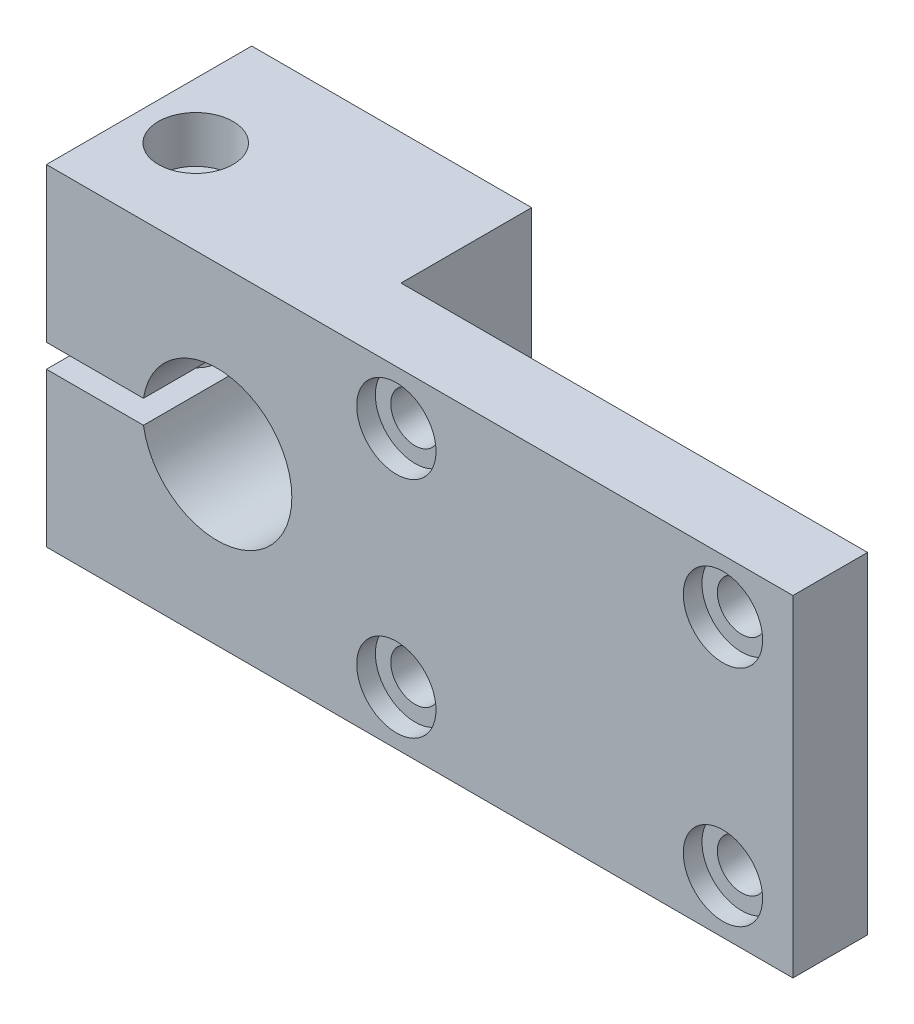
SolidWorks part; units mm, degrees
ref_plane "Plan de face" through (0, 0, 0) normal (0, 0, 1) x (1, 0, 0)
ref_plane "Plan de dessus" through (0, 0, 0) normal (0, 1, 0) x (1, 0, 0)
ref_plane "Plan de droite" through (0, 0, 0) normal (1, 0, 0) x (0, 0, -1)
sketch "Esquisse1" plane through (0, 0, 0) normal (0, 0, 1) x (1, 0, 0)
  line L4 (25, 0) -> (-25, 0)
  line L5 (-25, 0) -> (-25, -31.5)
  line L6 (-25, -31.5) -> (25, -31.5)
  line L7 (25, -31.5) -> (25, 0)
  line L8 (25, 0) -> (-25, 0)
  line L9 (-25, 0) -> (-25, -31.5)
  line L10 (-25, -31.5) -> (25, -31.5)
  line L11 (25, -31.5) -> (25, 0)
  circle A0 centre (17.5, -27.75) radius 2.1 construction
  circle A1 centre (17.5, -3.75) radius 2.1 construction
  circle A2 centre (-17.5, -3.75) radius 2.1 construction
  circle A3 centre (-17.5, -27.75) radius 2.1 construction
  circle A4 centre (17.5, -27.75) radius 2.1
  circle A5 centre (17.5, -3.75) radius 2.1
  circle A6 centre (-17.5, -3.75) radius 2.1
  circle A7 centre (-17.5, -27.75) radius 2.1
  dimension "D1" = 0
extrude "Boss.-Extru.1" add sketch "Esquisse1" along normal blind 8
sketch "Esquisse3" plane through (-25, 0, 0) normal (-1, 0, 0) x (0, 0, 1)
  line L1 (8, -31.5) -> (-36, -31.5)
  line L2 (8, -31.5) -> (8, 0)
  line L3 (8, 0) -> (-36, 0)
  line L4 (-36, -31.5) -> (-36, 0)
extrude "Boss.-Extru.2" add sketch "Esquisse3" along normal blind 30
sketch "Esquisse4" plane through (0, 0, 8) normal (0, 0, 1) x (1, 0, 0)
  line L0 (-21.7, -31.5) -> (-21.7, 0) construction
  line L1 (-55, -31.5) -> (25, -31.5) construction
  line L2 (25, 0) -> (-55, 0) construction
  line L3 (-55, -15.75) -> (-21.7, -15.75) construction
  line L4 (-55, -31.5) -> (-55, 0) construction
  circle A0 centre (-36.7, -15.75) radius 8
  circle A2 centre (-17.5, -27.75) radius 2.1 construction
  dimension "D1" = 4.2
  dimension "D2" = 16
  dimension "D3" = 15
extrude "Enlèv. mat.-Extru.1" cut sketch "Esquisse4" against normal blind 60
sketch "Esquisse6" plane through (0, 0, 8) normal (0, 0, 1) x (1, 0, 0)
  line L0 (-55, -15.75) -> (-21.7, -15.75) construction
  line L1 (-55, -31.5) -> (-55, 0) construction
  line L2 (-21.7, -15.75) -> (-21.7, 0) construction
  line L3 (25, 0) -> (-55, 0) construction
  line L4 (-55, -14.5) -> (-44.6017, -14.5)
  line L5 (-55, -17) -> (-44.6017, -17)
  line L6 (-55, -14.5) -> (-55, -17)
  circle A0 centre (-36.7, -15.75) radius 8 construction
  arc A1 (-44.6017, -14.5) -> (-44.6017, -17) centre (-36.7, -15.75) ccw
  dimension "D3" = 1.25
  dimension "D1" = 15
  dimension "D2" = 1.25
extrude "Enlèv. mat.-Extru.2" cut sketch "Esquisse6" against normal blind 56
sketch "Esquisse7" plane through (0, 0, 8) normal (0, 0, 1) x (1, 0, 0)
  circle A0 centre (-17.5, -3.75) radius 3.6
  circle A1 centre (-17.5, -27.75) radius 3.6
  circle A2 centre (17.5, -27.75) radius 3.6
  circle A3 centre (17.5, -3.75) radius 3.6
  circle A4 centre (17.5, -3.75) radius 2.1 construction
  circle A5 centre (17.5, -27.75) radius 2.1 construction
  circle A6 centre (-17.5, -27.75) radius 2.1 construction
  dimension "D1" = 7.2
  dimension "D2" = 7.2
  dimension "D3" = 7.2
  dimension "D4" = 7.2
extrude "Enlèv. mat.-Extru.3" cut sketch "Esquisse7" against normal blind 2
hole_wizard "Dégagement M51" positions "Esquisse10" profile "Esquisse11" hole size "M5" standard "Ansi Metric"
sketch "Esquisse10" plane through (0, 0, 0) normal (0, 1, 0) x (1, 0, 0)
  line L0 (-55, -8) -> (-55, 36) construction
  line L1 (25, -8) -> (-55, -8) construction
  point P0 (-49, 2)
  dimension "D1" = 6
  dimension "D2" = 10
sketch "Esquisse11" plane through (-49, 0, -2) normal (1, 0, 0) x (0, 0, 1)
  line L0 (0, 0) -> (0, 35.5923)
  line L1 (0, 35.5923) -> (2.65, 34)
  line L2 (2.65, 34) -> (2.65, 0)
  line L5 (2.65, 0) -> (0, 0)
  line L10 (0, 35.5923) -> (-2.65, 34) construction
  line L11 (0, -6.35) -> (0, 107.95) construction
  dimension "Diamètre du perçage" = 5.3
  dimension "Profondeur du perçage" = 34
  dimension "Angle de pointe" = 118
sketch "Esquisse12" plane through (0, -31.5, 0) normal (0, -1, 0) x (1, 0, 0)
  line L0 (-49, -2) -> (-49, 8) construction
  line L1 (-45, 0.3094) -> (-49, 2.6188)
  line L2 (-49, 2.6188) -> (-53, 0.3094)
  line L3 (-53, 0.3094) -> (-53, -4.3094)
  line L4 (-53, -4.3094) -> (-49, -6.6188)
  line L5 (-49, -6.6188) -> (-45, -4.3094)
  line L6 (-45, -4.3094) -> (-45, 0.3094)
  line L7 (-55, 8) -> (25, 8) construction
  line L8 (-55, -36) -> (-55, 8) construction
  circle A0 centre (-49, -2) radius 4 construction
  dimension "D3" = 10
  dimension "D1" = 8
  dimension "D2" = 10
  dimension "D4" = 6
extrude "Enlèv. mat.-Extru.4" cut sketch "Esquisse12" against normal blind 8
sketch "Esquisse13" plane through (0, -31.5, 0) normal (0, -1, 0) x (1, 0, 0)
  line L0 (-55, -36) -> (-55, 8) construction
  line L1 (-55, -14) -> (-25, -14)
  line L2 (-55, -14) -> (-55, -36)
  line L3 (-55, -36) -> (-25, -36)
  line L4 (-25, -14) -> (-25, -36)
  line L5 (-55, -36) -> (-25, -36) construction
  line L7 (-55, 8) -> (25, 8) construction
  line L8 (-25, -36) -> (-25, 0) construction
  dimension "D2" = 22
extrude "Enlèv. mat.-Extru.6" cut sketch "Esquisse13" against normal blind 58
sketch "Esquisse14" plane through (0, 0, 0) normal (0, 1, 0) x (1, 0, 0)
  circle A0 centre (-49, 2) radius 4
  dimension "D1" = 8
extrude "Enlèv. mat.-Extru.7" cut sketch "Esquisse14" against normal blind 3
sketch "Esquisse15" plane through (-55, 0, 0) normal (-1, 0, 0) x (0, 0, 1)
  line L1 (-14, 0) -> (-14, -14.5) construction
  line L2 (-14, -31.5) -> (8, -31.5) construction
  circle A0 centre (4, -20.5) radius 1.25
  dimension "D1" = 2.5
  dimension "D2" = 18
  dimension "D3" = 11
extrude "Enlèv. mat.-Extru.8" cut sketch "Esquisse15" against normal blind 5
sketch "Esquisse16" plane through (0, -31.5, 0) normal (0, -1, 0) x (1, 0, 0)
  line L0 (-53, 0.3094) -> (-53, -4.3094) construction
  line L1 (-49, 2.6188) -> (-53, 0.3094) construction
  line L2 (-45, 0.3094) -> (-49, 2.6188) construction
  line L3 (-45, -4.3094) -> (-45, 0.3094) construction
  line L4 (-49, -6.6188) -> (-45, -4.3094) construction
  line L5 (-53, -4.3094) -> (-49, -6.6188) construction
  line L6 (-55, 8) -> (-55, -14)
  line L7 (-55, -14) -> (-25, -14)
  line L8 (-25, -14) -> (-25, 0)
  line L9 (-25, 0) -> (25, 0)
  line L10 (25, 0) -> (25, 8)
  line L11 (25, 8) -> (-55, 8)
  line L12 (-55, 8) -> (-55, -14)
  line L13 (-55, -14) -> (-25, -14)
  line L14 (-25, -14) -> (-25, 0)
  line L15 (-25, 0) -> (25, 0)
  line L16 (25, 0) -> (25, 8)
  line L17 (25, 8) -> (-55, 8)
  line L18 (-53, 0.3094) -> (-53, -4.3094)
  line L19 (-49, 2.6188) -> (-53, 0.3094)
  line L20 (-45, 0.3094) -> (-49, 2.6188)
  line L21 (-45, -4.3094) -> (-45, 0.3094)
  line L22 (-49, -6.6188) -> (-45, -4.3094)
  line L23 (-53, -4.3094) -> (-49, -6.6188)
  dimension "D1" = 0
extrude "Boss.-Extru.3" add sketch "Esquisse16" along normal blind 2
sketch "Esquisse17" plane through (0, 0, 0) normal (0, 1, 0) x (1, 0, 0)
  line L6 (-25, 0) -> (-25, 14)
  line L7 (-25, 14) -> (-55, 14)
  line L8 (-55, 14) -> (-55, -8)
  line L9 (-55, -8) -> (25, -8)
  line L10 (25, -8) -> (25, 0)
  line L11 (25, 0) -> (-25, 0)
  line L12 (-25, 0) -> (-25, 14)
  line L13 (-25, 14) -> (-55, 14)
  line L14 (-55, 14) -> (-55, -8)
  line L15 (-55, -8) -> (25, -8)
  line L16 (25, -8) -> (25, 0)
  line L17 (25, 0) -> (-25, 0)
  circle A0 centre (-49, 2) radius 4 construction
  circle A1 centre (-49, 2) radius 4
  dimension "D1" = 0
extrude "Boss.-Extru.4" add sketch "Esquisse17" along normal blind 2
sketch "Esquisse18" plane through (0, 0, 8) normal (0, 0, 1) x (1, 0, 0)
  circle A0 centre (-17.5, -3.75) radius 2.6
  circle A1 centre (17.5, -3.75) radius 2.6
  circle A2 centre (17.5, -27.75) radius 2.6
  circle A3 centre (-17.5, -27.75) radius 2.6
  dimension "D1" = 5.2
  dimension "D2" = 5.2
  dimension "D3" = 5.2
  dimension "D4" = 5.2
extrude "Enlèv. mat.-Extru.9" cut sketch "Esquisse18" against normal blind 22
sketch "Esquisse19" plane through (0, 0, 8) normal (0, 0, 1) x (1, 0, 0)
  circle A0 centre (-17.5, -3.75) radius 4.25
  circle A1 centre (17.5, -3.75) radius 4.25
  circle A2 centre (17.5, -27.75) radius 4.25
  circle A3 centre (-17.5, -27.75) radius 4.25
  dimension "D1" = 8.5
  dimension "D2" = 8.5
  dimension "D3" = 8.5
  dimension "D4" = 8.5
extrude "Enlèv. mat.-Extru.10" cut sketch "Esquisse19" against normal blind 2
